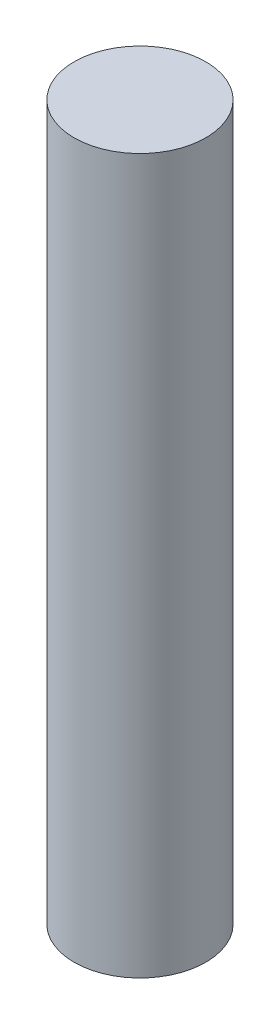
SolidWorks part; units mm, degrees
ref_plane "Alzado" through (0, 0, 0) normal (0, 0, 1) x (1, 0, 0)
ref_plane "Planta" through (0, 0, 0) normal (0, 1, 0) x (1, 0, 0)
ref_plane "Vista lateral" through (0, 0, 0) normal (1, 0, 0) x (0, 0, -1)
ref_plane "Plano_TuboTelescopio" through (0, 152.5, 0) normal (0, 1, 0) x (1, 0, 0)
sketch "SkTuboTelescopio" plane through (0, 152.5, 0) normal (0, 1, 0) x (1, 0, 0)
  circle A0 centre (0, 0) radius 125
extrude "TuboTelescopio" add sketch "SkTuboTelescopio" along normal blind 1355 separate body
